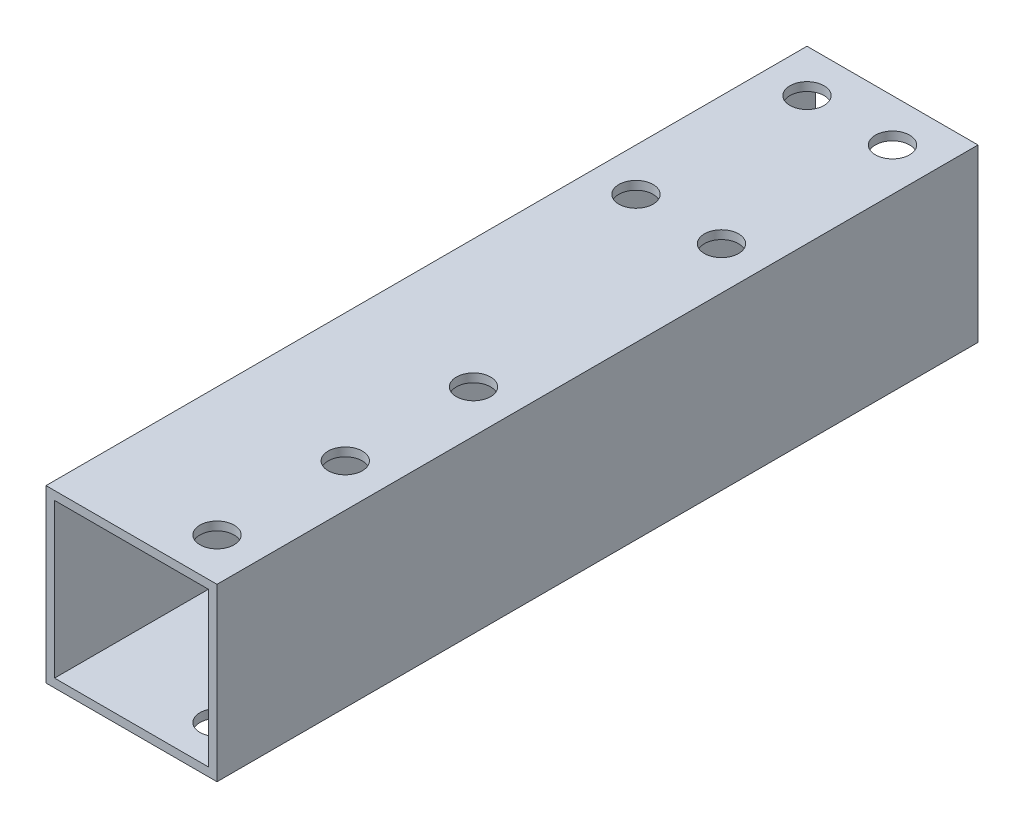
SolidWorks part; units mm, degrees
ref_plane "前视基准面" through (0, 0, 0) normal (0, 0, 1) x (1, 0, 0)
ref_plane "上视基准面" through (0, 0, 0) normal (0, 1, 0) x (1, 0, 0)
ref_plane "右视基准面" through (0, 0, 0) normal (1, 0, 0) x (0, 0, -1)
sketch "草图1" plane through (0, 0, 0) normal (0, 0, 1) x (1, 0, 0)
  line L1 (0, 0) -> (20, 0)
  line L2 (0, 0) -> (0, 20)
  line L3 (0, 20) -> (20, 20)
  line L4 (20, 0) -> (20, 20)
  dimension "D1" = 20
  dimension "D2" = 20
extrude "拉伸-薄壁1" add sketch "草图1" along normal blind 89 thin thin type one direction reverse wall 1
sketch "草图2" plane through (0, 20, 0) normal (0, 1, 0) x (1, 0, 0)
  line L0 (20, 0) -> (0, 0) construction
  line L1 (5, -5) -> (15, -5) construction
  line L2 (5, -5) -> (5, -25) construction
  line L3 (5, -25) -> (15, -25) construction
  line L4 (15, -5) -> (15, -25) construction
  line L5 (0, -89) -> (0, 0) construction
  line L6 (20, -89) -> (20, 0) construction
  line L7 (15, -89) -> (15, -25) construction
  line L8 (20, -89) -> (0, -89) construction
  circle A0 centre (5, -5) radius 2
  circle A1 centre (15, -5) radius 2
  circle A2 centre (5, -25) radius 2
  circle A3 centre (15, -25) radius 2
  circle A4 centre (15, -84) radius 2
  circle A5 centre (15, -69) radius 2
  circle A6 centre (15, -54) radius 2
  dimension "D5" = 4
  dimension "D6" = 4
  dimension "D7" = 5
  dimension "D1" = 5
  dimension "D2" = 5
  dimension "D3" = 5
  dimension "D4" = 20
  dimension "D8" = 15
  dimension "D9" = 15
extrude "切除-拉伸1" cut sketch "草图2" against normal through all
